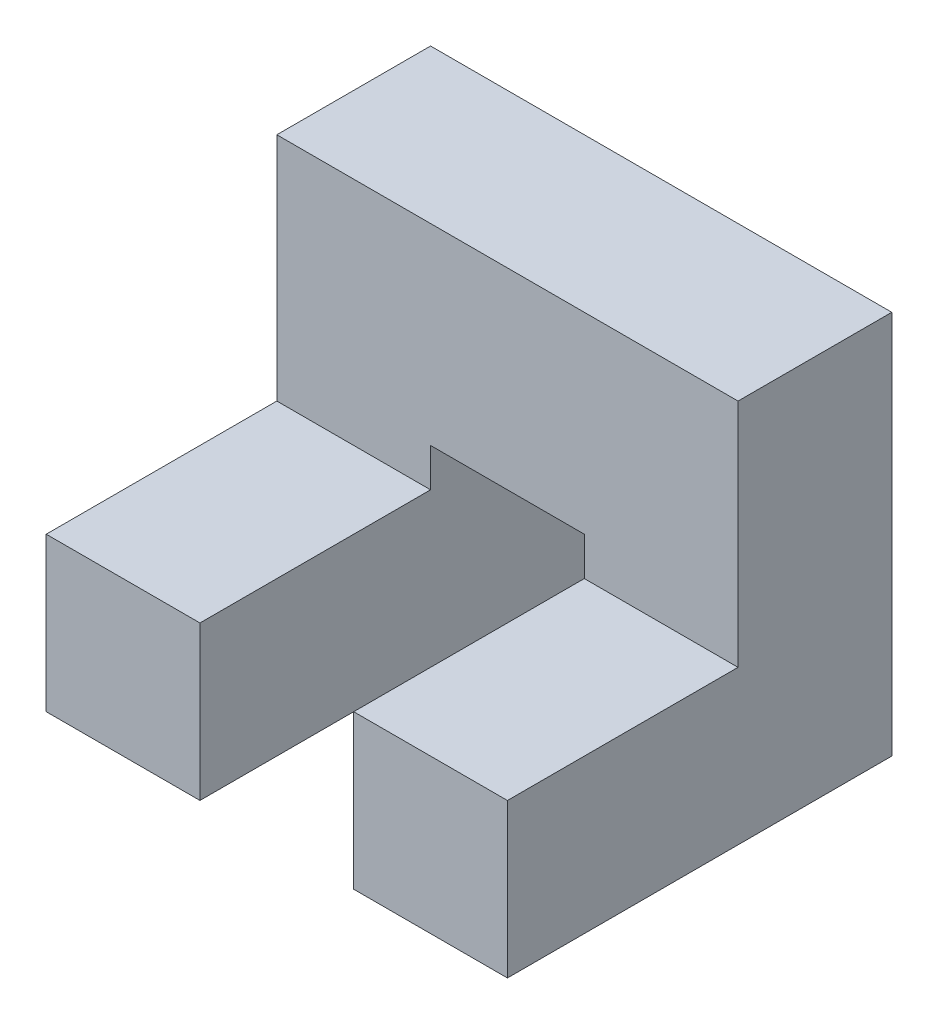
SolidWorks part; units mm, degrees
ref_plane "Alzado" through (0, 0, 0) normal (0, 0, 1) x (1, 0, 0)
ref_plane "Planta" through (0, 0, 0) normal (0, 1, 0) x (1, 0, 0)
ref_plane "Vista lateral" through (0, 0, 0) normal (1, 0, 0) x (0, 0, -1)
sketch "Croquis2" plane through (0, 0, 0) normal (0, 0, 1) x (1, 0, 0)
  line L1 (-30, -25) -> (30, -25)
  line L2 (-30, -25) -> (-30, 25)
  line L3 (-30, 25) -> (30, 25)
  line L4 (30, -25) -> (30, 25)
  line L5 (-30, -25) -> (30, 25) construction
  line L6 (-30, 25) -> (30, -25) construction
  point P0 (0, 0)
  dimension "D1" = 50
  dimension "D2" = 60
extrude "Saliente-Extruir1" add sketch "Croquis2" along normal blind 50
sketch "Croquis3" plane through (0, 25, 0) normal (0, 1, 0) x (1, 0, 0)
  line L0 (30, -50) -> (-30, -50) construction
  line L1 (-30, -50) -> (30, -50)
  line L2 (-30, -50) -> (-30, -20)
  line L3 (-30, -20) -> (30, -20)
  line L4 (30, -50) -> (30, -20)
  line L5 (30, -50) -> (30, 0) construction
  dimension "D1" = 30
  dimension "D2" = 60
extrude "Cortar-Extruir1" cut sketch "Croquis3" against normal blind 35
sketch "Croquis4" plane through (0, 0, 0) normal (0, 0, -1) x (-1, 0, 0)
  line L0 (30, -25) -> (-30, -25) construction
  line L1 (-10, -25) -> (10, -25)
  line L2 (-10, -25) -> (-10, 0)
  line L3 (-10, 0) -> (10, 0)
  line L4 (10, -25) -> (10, 0)
  line L6 (30, 25) -> (30, -25) construction
  dimension "D1" = 25
  dimension "D2" = 20
  dimension "D3" = 20
extrude "Cortar-Extruir2" cut sketch "Croquis4" against normal blind 50
sketch "Croquis5" plane through (0, -10, 0) normal (0, 1, 0) x (1, 0, 0)
  line L1 (10, -20) -> (30, -20)
  line L2 (10, -20) -> (10, -50)
  line L3 (10, -50) -> (30, -50)
  line L4 (30, -20) -> (30, -50)
  line L5 (-10, -20) -> (-30, -20)
  line L6 (-10, -20) -> (-10, -50)
  line L7 (-10, -50) -> (-30, -50)
  line L8 (-30, -20) -> (-30, -50)
extrude "Saliente-Extruir2" add sketch "Croquis5" along normal blind 5
